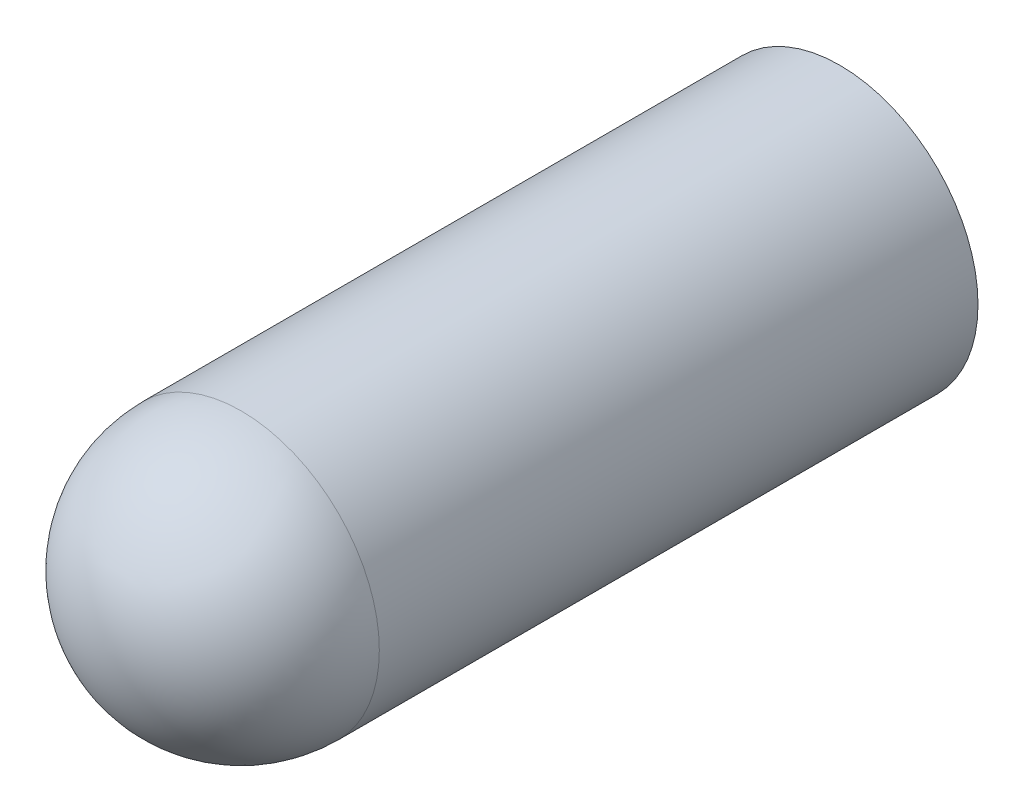
SolidWorks part; units mm, degrees
ref_plane "前视基准面" through (0, 0, 0) normal (0, 0, 1) x (1, 0, 0)
ref_plane "上视基准面" through (0, 0, 0) normal (0, 1, 0) x (1, 0, 0)
ref_plane "右视基准面" through (0, 0, 0) normal (1, 0, 0) x (0, 0, -1)
sketch "草图1" plane through (0, 0, 0) normal (0, 0, 1) x (1, 0, 0)
  circle A0 centre (0, 0) radius 1.5
  dimension "D1" = 3
extrude "凸台-拉伸1" add sketch "草图1" along normal blind 8
fillet "圆角1" radius 1.5 1 edges at (1.5, 0, 8)
